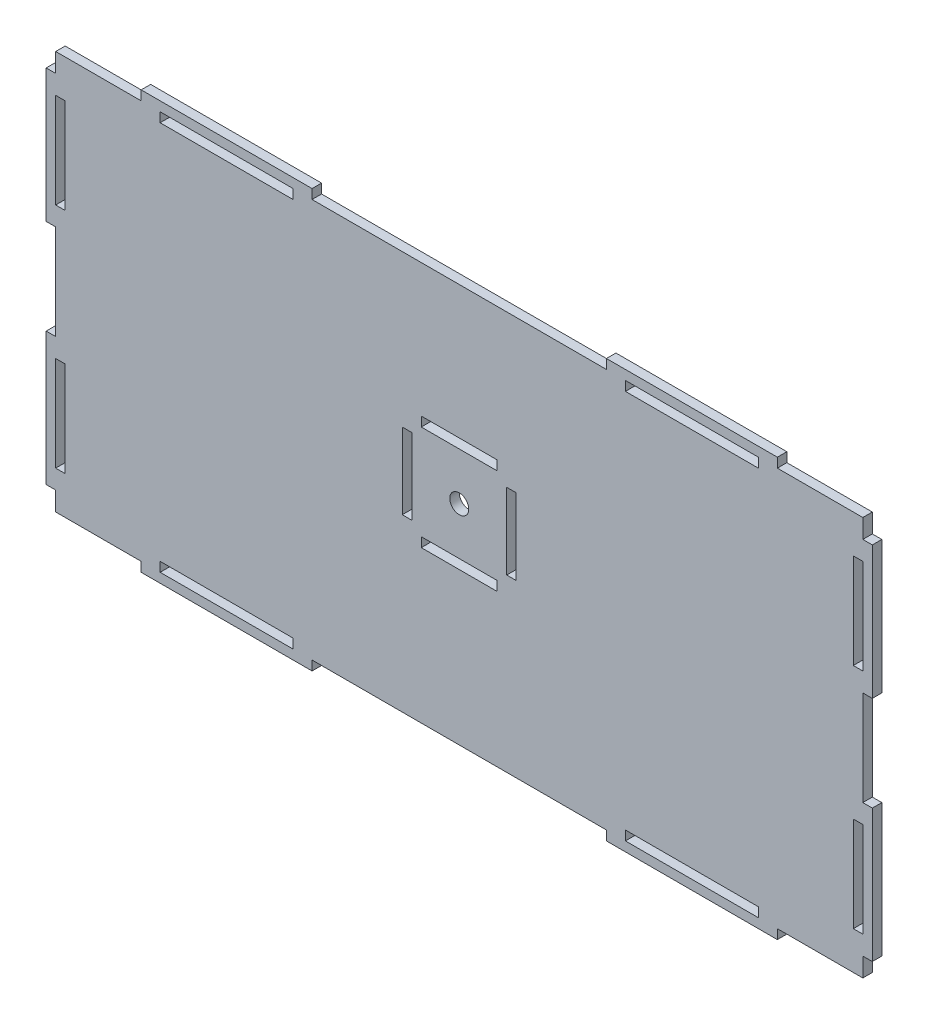
SolidWorks part; units mm, degrees
ref_plane "Front Plane" through (0, 0, 0) normal (0, 0, 1) x (1, 0, 0)
ref_plane "Top Plane" through (0, 0, 0) normal (0, 1, 0) x (1, 0, 0)
ref_plane "Right Plane" through (0, 0, 0) normal (1, 0, 0) x (0, 0, -1)
sketch "Sketch1" plane through (0, 0, 0) normal (0, 0, 1) x (1, 0, 0)
  line L0 (-212.5, 210) -> (-212.5, 88.8289) construction
  line L1 (0, 0) -> (-425, 0)
  line L2 (0, 0) -> (0, 210)
  line L3 (0, 210) -> (-425, 210)
  line L4 (-425, 0) -> (-425, 210)
  line L6 (-217.5, 210) -> (-207.5, 210) construction
  line L7 (-217.5, 210) -> (-217.5, 110) construction
  line L8 (-217.5, 110) -> (-207.5, 110) construction
  line L9 (-207.5, 210) -> (-207.5, 110) construction
  circle A0 centre (-212.5, 110) radius 5
  point P11 (-212.5, 110)
  dimension "D1" = 210
  dimension "D2" = 425
  dimension "D3" = 100
  dimension "D4" = 10
extrude "Boss-Extrude1" add sketch "Sketch1" along normal blind 5
sketch "Sketch2" plane through (0, 0, 0) normal (0, 0, -1) x (-1, 0, 0)
  line L0 (425, 0) -> (0, 0) construction
  line L1 (125, 0) -> (55, 0)
  line L2 (125, 0) -> (125, 5)
  line L3 (125, 5) -> (55, 5)
  line L4 (55, 0) -> (55, 5)
  line L5 (0, 0) -> (0, 210) construction
  line L6 (212.5, 0) -> (212.5, 60.0413) construction
  line L7 (0, 105) -> (55, 105) construction
  line L8 (0, 70) -> (5, 70)
  line L9 (0, 70) -> (0, 20)
  line L10 (0, 20) -> (5, 20)
  line L11 (5, 70) -> (5, 20)
  line L12 (0, 190) -> (5, 190)
  line L13 (5, 140) -> (5, 190)
  line L14 (0, 140) -> (5, 140)
  line L15 (0, 140) -> (0, 190)
  line L16 (125, 205) -> (55, 205)
  line L17 (55, 210) -> (55, 205)
  line L18 (125, 210) -> (55, 210)
  line L19 (125, 210) -> (125, 205)
  line L20 (125, 0) -> (125, 5)
  line L21 (125, 0) -> (55, 0)
  line L22 (55, 0) -> (55, 5)
  line L23 (125, 5) -> (55, 5)
  line L24 (0, 70) -> (0, 20)
  line L25 (0, 70) -> (5, 70)
  line L26 (5, 70) -> (5, 20)
  line L27 (0, 20) -> (5, 20)
  line L28 (5, 140) -> (5, 190)
  line L29 (0, 190) -> (5, 190)
  line L30 (0, 140) -> (0, 190)
  line L31 (0, 140) -> (5, 140)
  line L32 (55, 210) -> (55, 205)
  line L33 (125, 205) -> (55, 205)
  line L34 (125, 210) -> (125, 205)
  line L35 (125, 210) -> (55, 210)
  line L36 (425, 105) -> (370, 105) construction
  line L37 (300, 210) -> (370, 210)
  line L38 (300, 210) -> (300, 205)
  line L39 (300, 205) -> (370, 205)
  line L40 (370, 210) -> (370, 205)
  line L41 (425, 140) -> (420, 140)
  line L42 (425, 140) -> (425, 190)
  line L43 (425, 190) -> (420, 190)
  line L44 (420, 140) -> (420, 190)
  line L45 (425, 20) -> (420, 20)
  line L46 (420, 70) -> (420, 20)
  line L47 (425, 70) -> (420, 70)
  line L48 (425, 70) -> (425, 20)
  line L49 (300, 5) -> (370, 5)
  line L50 (370, 0) -> (370, 5)
  line L51 (300, 0) -> (370, 0)
  line L52 (300, 0) -> (300, 5)
  line L53 (300, 210) -> (300, 205)
  line L54 (300, 210) -> (370, 210)
  line L55 (370, 210) -> (370, 205)
  line L56 (300, 205) -> (370, 205)
  line L57 (425, 140) -> (425, 190)
  line L58 (425, 140) -> (420, 140)
  line L59 (420, 140) -> (420, 190)
  line L60 (425, 190) -> (420, 190)
  line L61 (420, 70) -> (420, 20)
  line L62 (425, 20) -> (420, 20)
  line L63 (425, 70) -> (425, 20)
  line L64 (425, 70) -> (420, 70)
  line L65 (370, 0) -> (370, 5)
  line L66 (300, 5) -> (370, 5)
  line L67 (300, 0) -> (300, 5)
  line L68 (300, 0) -> (370, 0)
  line M11 (0, 210) -> (0, 0)
  line M12 (0, 0) -> (425, 0)
  line M13 (425, 0) -> (425, 210)
  line M14 (425, 210) -> (0, 210)
  dimension "D1" = 70
  dimension "D2" = 55
  dimension "D3" = 5
  dimension "D4" = 20
  dimension "D5" = 50
  dimension "D6" = 5
extrude "Cut-Extrude1" cut sketch "Sketch2" against normal blind 5 contours L47 L46 L45 M13 | L52 L50 L49 M12 | L44 L41 L43 M13 | L40 L38 L39 M14 | L19 L17 L16 M14 | L14 L13 L12 M11 | L4 L2 L3 M12 | L11 L8 L10 M11 | L18
sketch "Sketch3" plane through (0, 0, 5) normal (0, 0, 1) x (1, 0, 0)
  line L0 (-125, 210) -> (-300, 210) construction
  line L1 (-290, 210) -> (-380, 210)
  line L2 (-290, 210) -> (-290, 215)
  line L3 (-290, 215) -> (-380, 215)
  line L4 (-380, 210) -> (-380, 215)
  line L5 (-300, 210) -> (-300, 205) construction
  line L6 (-212.5, 210) -> (-212.5, 290.4842) construction
  line L7 (-45, 210) -> (-45, 215)
  line L8 (-135, 215) -> (-45, 215)
  line L9 (-135, 210) -> (-135, 215)
  line L10 (-135, 210) -> (-45, 210)
  line L11 (0, 105) -> (-117.9056, 105) construction
  line L12 (0, 70) -> (0, 140) construction
  line L13 (-380, 0) -> (-380, -5)
  line L14 (-290, -5) -> (-380, -5)
  line L15 (-290, 0) -> (-290, -5)
  line L16 (-290, 0) -> (-380, 0)
  line L17 (-135, 0) -> (-45, 0)
  line L18 (-135, 0) -> (-135, -5)
  line L19 (-135, -5) -> (-45, -5)
  line L20 (-45, 0) -> (-45, -5)
  dimension "D1" = 90
  dimension "D2" = 10
  dimension "D3" = 5
extrude "Boss-Extrude2" add sketch "Sketch3" against normal blind 5
sketch "Sketch4" plane through (0, 0, 5) normal (0, 0, 1) x (1, 0, 0)
  line L0 (-425, 210) -> (-425, 190) construction
  line L1 (-425, 200) -> (-430, 200)
  line L2 (-425, 200) -> (-425, 130)
  line L3 (-425, 130) -> (-430, 130)
  line L4 (-430, 200) -> (-430, 130)
  line L5 (-425, 190) -> (-420, 190) construction
  line L6 (-425, 105) -> (-465.1564, 105) construction
  line L7 (-425, 140) -> (-425, 70) construction
  line L8 (-430, 10) -> (-430, 80)
  line L9 (-425, 80) -> (-430, 80)
  line L10 (-425, 10) -> (-425, 80)
  line L11 (-425, 10) -> (-430, 10)
  line L12 (-212.5, 210) -> (-212.5, 271.7144) construction
  line L13 (-135, 210) -> (-290, 210) construction
  line L14 (0, 105) -> (40.1564, 105) construction
  line L15 (0, 10) -> (5, 10)
  line L16 (0, 10) -> (0, 80)
  line L17 (0, 80) -> (5, 80)
  line L18 (5, 10) -> (5, 80)
  line L19 (5, 200) -> (5, 130)
  line L20 (0, 130) -> (5, 130)
  line L21 (0, 200) -> (0, 130)
  line L22 (0, 200) -> (5, 200)
  dimension "D1" = 70
  dimension "D2" = 5
  dimension "D3" = 10
extrude "Boss-Extrude3" add sketch "Sketch4" against normal blind 5
sketch "Sketch5" plane through (0, 0, 5) normal (0, 0, 1) x (1, 0, 0)
  line L0 (-212.5, 110) -> (-227.3064, 110) construction
  line L1 (-237.5, 90) -> (-242.5, 90)
  line L2 (-237.5, 90) -> (-237.5, 130)
  line L3 (-237.5, 130) -> (-242.5, 130)
  line L4 (-242.5, 90) -> (-242.5, 130)
  line L5 (-192.5, 85) -> (-232.5, 85)
  line L6 (-192.5, 85) -> (-192.5, 80)
  line L7 (-192.5, 80) -> (-232.5, 80)
  line L8 (-232.5, 85) -> (-232.5, 80)
  line L9 (-232.5, 135) -> (-232.5, 140)
  line L10 (-192.5, 140) -> (-232.5, 140)
  line L11 (-192.5, 135) -> (-192.5, 140)
  line L12 (-192.5, 135) -> (-232.5, 135)
  line L13 (-212.5, 110) -> (-212.5, 127.4796) construction
  line L14 (-182.5, 90) -> (-182.5, 130)
  line L15 (-187.5, 130) -> (-182.5, 130)
  line L16 (-187.5, 90) -> (-187.5, 130)
  line L17 (-187.5, 90) -> (-182.5, 90)
  point P4 (-212.5, 110)
  point P5 (-237.5, 110)
  point P11 (-212.5, 85)
  dimension "D1" = 40
  dimension "D2" = 5
  dimension "D3" = 25
  dimension "D4" = 25
  dimension "D5" = 40
  dimension "D6" = 5
extrude "Cut-Extrude2" cut sketch "Sketch5" against normal blind 5
